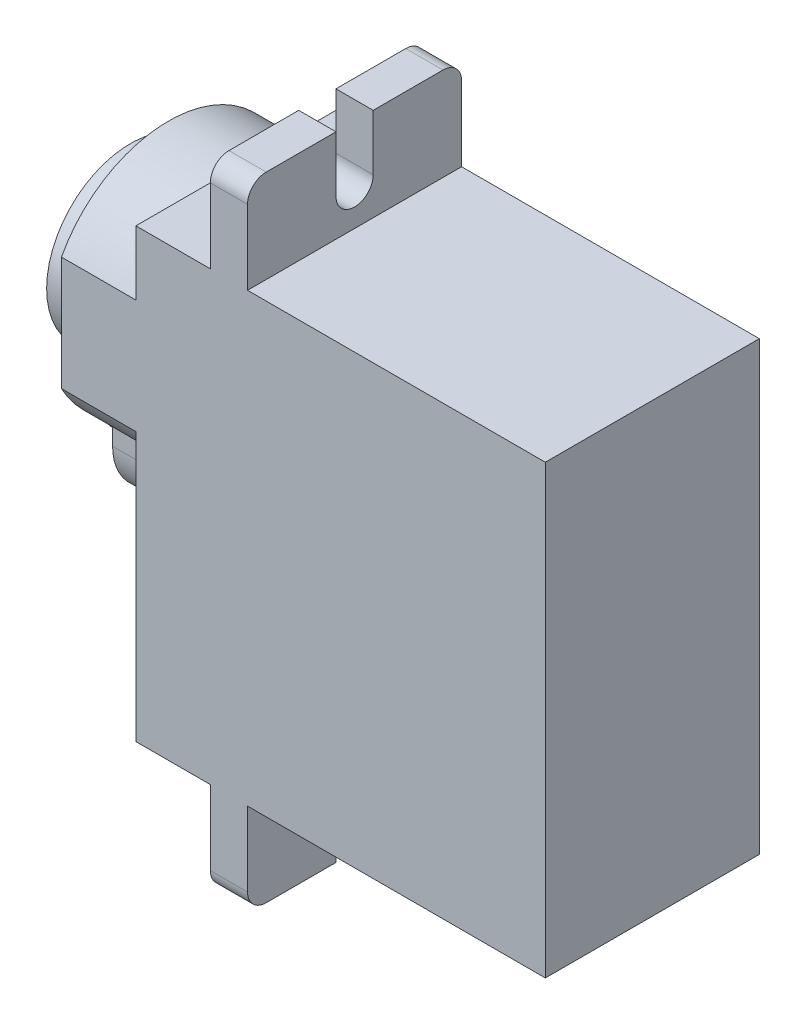
SolidWorks part; units mm, degrees
ref_plane "Plan de face" through (0, 0, 0) normal (0, 0, 1) x (1, 0, 0)
ref_plane "Plan de dessus" through (0, 0, 0) normal (0, 1, 0) x (1, 0, 0)
ref_plane "Plan de droite" through (0, 0, 0) normal (1, 0, 0) x (0, 0, -1)
sketch "Esquisse1" plane through (0, 0, 0) normal (0, 0, 1) x (1, 0, 0)
  line L0 (-8.4, 14.4) -> (-13.2, 14.4)
  line L1 (13.2, -14.4) -> (-6, -14.4)
  line L2 (13.2, -14.4) -> (13.2, 14.4)
  line L3 (13.2, 14.4) -> (-6, 14.4)
  line L4 (-13.2, -14.4) -> (-13.2, 14.4)
  line L5 (13.2, -14.4) -> (-13.2, 14.4) construction
  line L6 (13.2, 14.4) -> (-13.2, -14.4) construction
  line L8 (-8.4, -14.4) -> (-8.4, -20.4)
  line L9 (-8.4, -20.4) -> (-6, -20.4)
  line L10 (-6, -14.4) -> (-6, -20.4)
  line L12 (-8.4, 14.4) -> (-8.4, 20.4)
  line L13 (-8.4, 20.4) -> (-6, 20.4)
  line L14 (-6, 14.4) -> (-6, 20.4)
  line L15 (-8.4, -14.4) -> (-13.2, -14.4)
  point P0 (0, 0)
  dimension "D1" = 28.8
  dimension "D2" = 26.4
  dimension "D3" = 21.6
  dimension "D4" = 21.6
  dimension "D5" = 6
  dimension "D6" = 6
  dimension "D7" = 2.4
  dimension "D8" = 2.4
extrude "Boss.-Extru.2" add sketch "Esquisse1" along normal blind 13.8
sketch "Esquisse3" plane through (-8.4, 0, 0) normal (-1, 0, 0) x (0, 0, 1)
  line L0 (5.7, 20.4) -> (5.7, 16.8)
  line L1 (13.8, 20.4) -> (0, 20.4) construction
  line L3 (8.1, 16.8) -> (8.1, 20.4)
  arc A0 (5.7, 16.8) -> (8.1, 16.8) centre (6.9, 16.8) ccw
  dimension "D5" = 1.2
  dimension "D1" = 2.4
  dimension "D2" = 5.7
  dimension "D3" = 5.7
  dimension "D4" = 3.6
extrude "Enlèv. mat.-Extru.1" cut sketch "Esquisse3" against normal blind 13.8 and the other way through all
fillet "Congé1" radius 1.2 2 edges at (-7.2, 20.4, 0) (-7.2, 20.4, 13.8)
sketch "Esquisse5" plane through (-8.4, 0, 0) normal (-1, 0, 0) x (0, 0, 1)
  line L0 (5.7, -20.4) -> (5.7, -16.8)
  line L1 (13.8, -20.4) -> (0, -20.4) construction
  line L3 (8.1, -16.8) -> (8.1, -20.4)
  arc A0 (8.1, -16.8) -> (5.7, -16.8) centre (6.9, -16.8) ccw
  line M5 (0, -20.4) -> (13.8, -20.4)
  dimension "D4" = 1.2
  dimension "D1" = 2.4
  dimension "D2" = 5.7
  dimension "D3" = 3.6
extrude "Enlèv. mat.-Extru.4" cut sketch "Esquisse5" against normal blind 13.8 and the other way through all contours L3 A0 L0 M5
fillet "Congé2" radius 1.2 2 edges at (-7.2, -20.4, 13.8) (-7.2, -20.4, 0)
sketch "Esquisse6" plane through (-13.2, 0, 0) normal (-1, 0, 0) x (0, 0, 1)
  line L0 (13.8, 14.4) -> (0, 14.4) construction
  line L1 (13.8, 14.4) -> (13.8, -14.4) construction
  line L2 (0, 14.4) -> (0, -1.9608) construction
  line L3 (0, 14.4) -> (0, -14.4) construction
  line L4 (13.8, 14.4) -> (13.8, -1.9608) construction
  line L5 (3.3, -1.9608) -> (3.3, -0.3553)
  line L6 (10.5, -1.9608) -> (10.5, -0.3553)
  line L7 (0, 10.2564) -> (0, 2.91)
  line L8 (13.8, 10.2564) -> (13.8, 2.91)
  arc A0 (0, 2.91) -> (3.3, -0.3553) centre (6.9, 6.5832) ccw
  arc A1 (3.3, -1.9608) -> (10.5, -1.9608) centre (6.9, -1.9608) ccw
  arc A2 (13.8, 10.2564) -> (0, 10.2564) centre (6.9, 6.5832) ccw
  arc A3 (10.5, -0.3553) -> (13.8, 2.91) centre (6.9, 6.5832) ccw
  dimension "D1" = 6.9
  dimension "D2" = 7.2
  dimension "D3" = 8.544
extrude "Boss.-Extru.4" add sketch "Esquisse6" along normal blind 4.8
sketch "Esquisse7" plane through (-18, 0, 0) normal (-1, 0, 0) x (0, 0, 1)
  line L0 (5.1, -1.9608) -> (5.1, 1.5001)
  line L1 (8.7, -1.9608) -> (8.7, 1.4619)
  arc A0 (8.7, 1.4619) -> (5.1, 1.5001) centre (6.9541, 6.5719) ccw
  arc A1 (5.1, -1.9608) -> (8.7, -1.9608) centre (6.9, -1.9608) ccw
  dimension "D1" = 10.8
  dimension "D2" = 3.6
extrude "Boss.-Extru.5" add sketch "Esquisse7" along normal blind 2.4
sketch "Esquisse8" plane through (-20.4, 0, 0) normal (-1, 0, 0) x (0, 0, 1)
  circle A0 centre (6.9541, 6.5719) radius 3
  dimension "D1" = 6
extrude "Enlèv. mat.-Extru.5" cut sketch "Esquisse8" against normal blind 12
